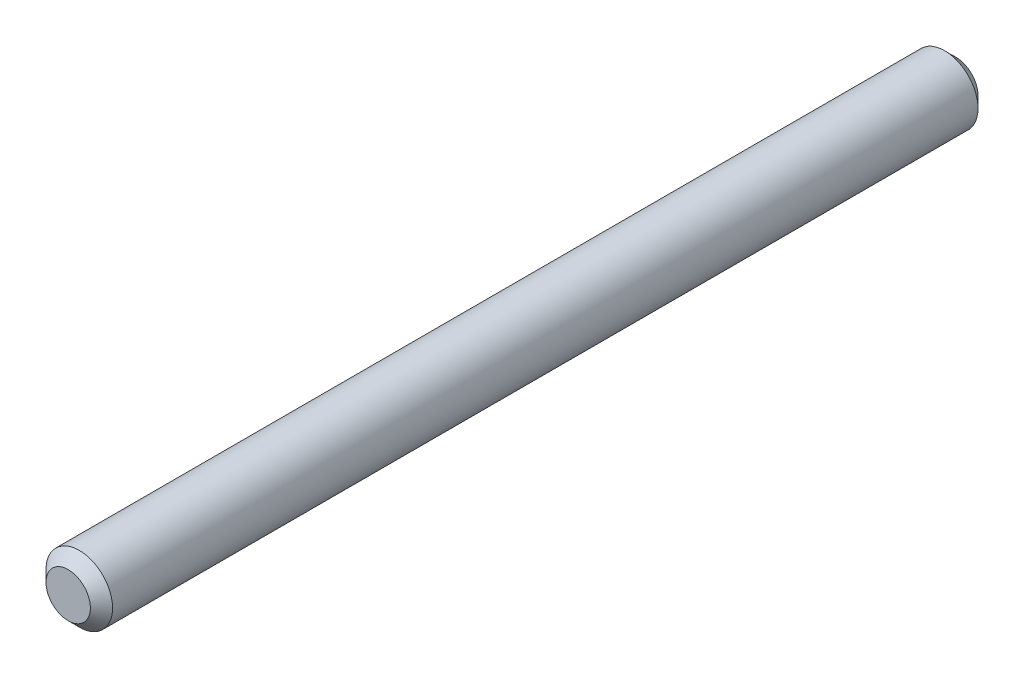
SolidWorks part; units mm, degrees
ref_plane "Alzado" through (0, 0, 0) normal (0, 0, 1) x (1, 0, 0)
ref_plane "Planta" through (0, 0, 0) normal (0, 1, 0) x (1, 0, 0)
ref_plane "Vista lateral" through (0, 0, 0) normal (1, 0, 0) x (0, 0, -1)
sketch "Croquis1" plane through (0, 0, 0) normal (0, 0, 1) x (1, 0, 0)
  circle A0 centre (0, 0) radius 3
  dimension "D1" = 6
extrude "Saliente-Extruir1" add sketch "Croquis1" along normal blind 80
chamfer "Chaflán1" distance 1 angle 45 2 edges at (3, 0, 0) (3, 0, 80)
